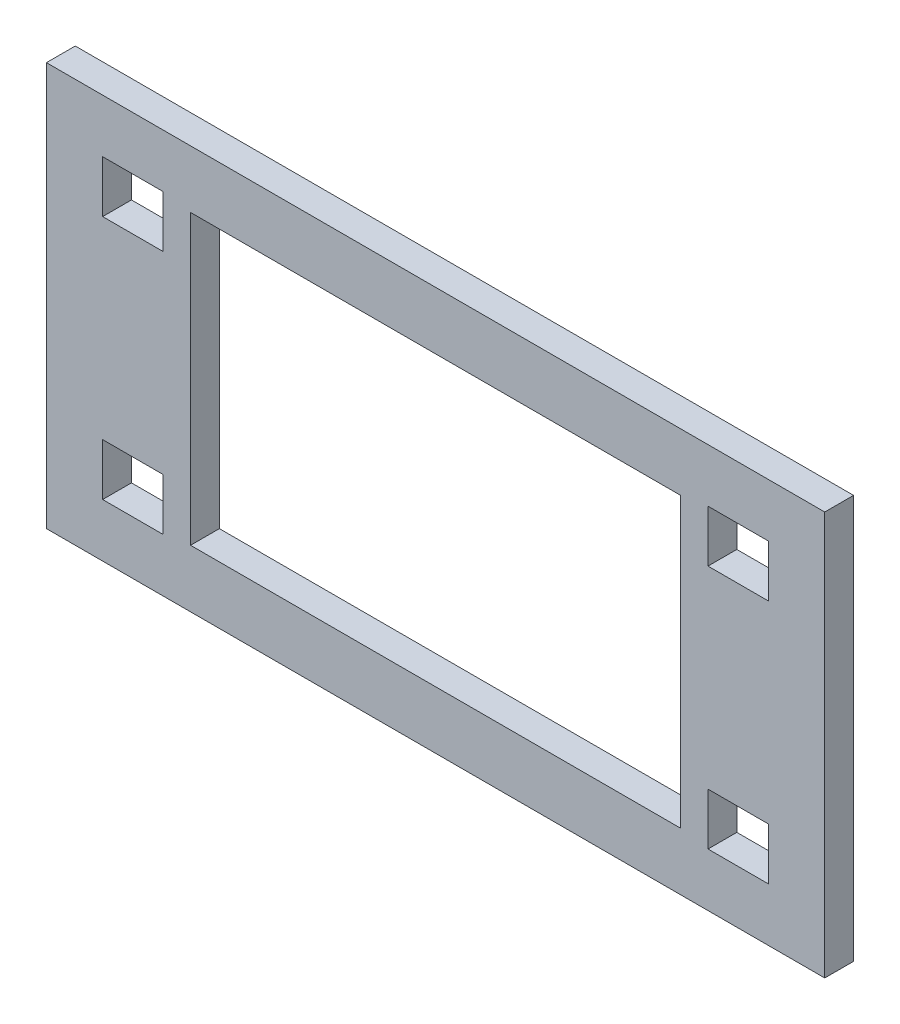
SolidWorks part; units mm, degrees
ref_plane "前视基准面" through (0, 0, 0) normal (0, 0, 1) x (1, 0, 0)
ref_plane "上视基准面" through (0, 0, 0) normal (0, 1, 0) x (1, 0, 0)
ref_plane "右视基准面" through (0, 0, 0) normal (1, 0, 0) x (0, 0, -1)
other "Configuration Table"
sketch "草图1" plane through (0, 0, 0) normal (0, 0, 1) x (1, 0, 0)
  line L0 (-27, -14) -> (27, -14)
  line L1 (27, -14) -> (27, 14)
  line L2 (27, 14) -> (-27, 14)
  line L3 (-27, 14) -> (-27, -14)
extrude "Gauge_plate_2mm" add sketch "草图1" along normal blind 2 from offset 0
sketch "草图2" plane through (0, 0, 0) normal (0, 0, 1) x (1, 0, 0)
  line L0 (-17, -10) -> (17, -10)
  line L1 (17, -10) -> (17, 10)
  line L2 (17, 10) -> (-17, 10)
  line L3 (-17, 10) -> (-17, -10)
extrude "Open_window" cut sketch "草图2" along normal blind 2.2 from offset 0.1
sketch "草图3" plane through (0, 0, 0) normal (0, 0, 1) x (1, 0, 0)
  line L0 (-23.1, -10.3) -> (-18.9, -10.3)
  line L1 (-18.9, -10.3) -> (-18.9, -6.7)
  line L2 (-18.9, -6.7) -> (-23.1, -6.7)
  line L3 (-23.1, -6.7) -> (-23.1, -10.3)
  line L4 (-23.1, 6.7) -> (-18.9, 6.7)
  line L5 (-18.9, 6.7) -> (-18.9, 10.3)
  line L6 (-18.9, 10.3) -> (-23.1, 10.3)
  line L7 (-23.1, 10.3) -> (-23.1, 6.7)
  line L8 (18.9, -10.3) -> (23.1, -10.3)
  line L9 (23.1, -10.3) -> (23.1, -6.7)
  line L10 (23.1, -6.7) -> (18.9, -6.7)
  line L11 (18.9, -6.7) -> (18.9, -10.3)
  line L12 (18.9, 6.7) -> (23.1, 6.7)
  line L13 (23.1, 6.7) -> (23.1, 10.3)
  line L14 (23.1, 10.3) -> (18.9, 10.3)
  line L15 (18.9, 10.3) -> (18.9, 6.7)
extrude "Same_slots_as_sensor_bracket_42x17" cut sketch "草图3" along normal blind 2.2 from offset 0.1
